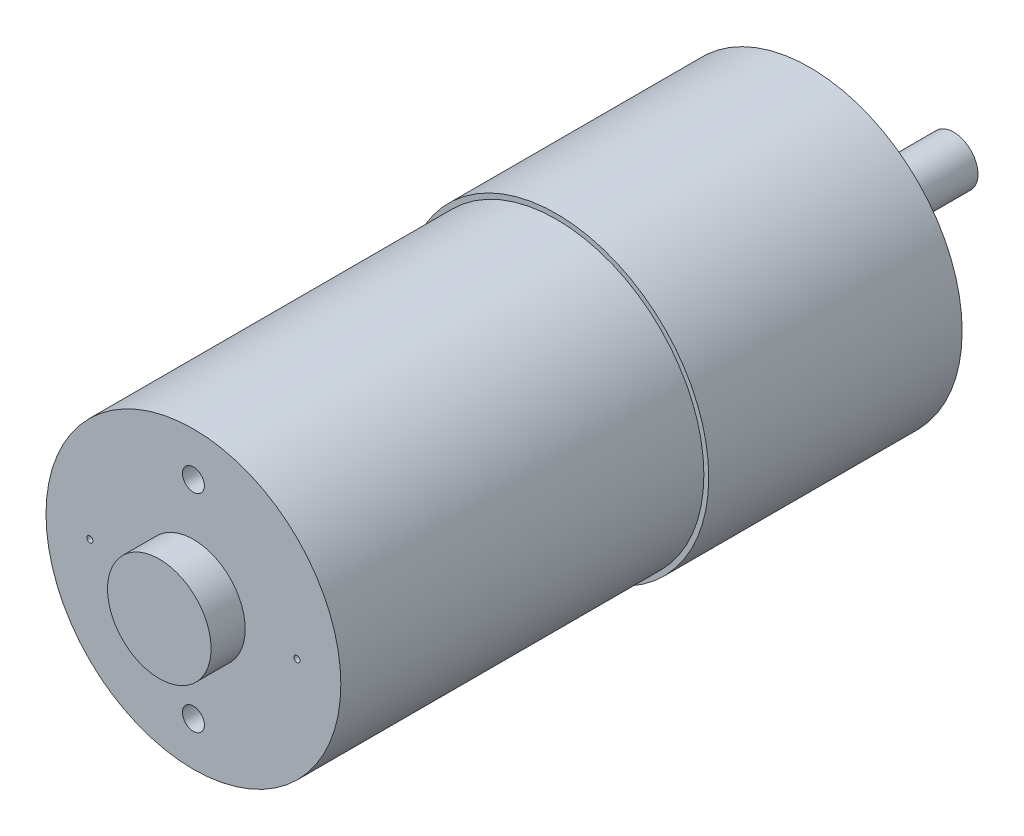
SolidWorks part; units mm, degrees
ref_plane "Plano frontal" through (0, 0, 0) normal (0, 0, 1) x (1, 0, 0)
ref_plane "Plano superior" through (0, 0, 0) normal (0, 1, 0) x (1, 0, 0)
ref_plane "Plano direito" through (0, 0, 0) normal (1, 0, 0) x (0, 0, -1)
sketch "Esboço1" plane through (0, 0, 0) normal (0, 0, 1) x (1, 0, 0)
  line L0 (0, 0) -> (0, 8.5) construction
  line L1 (0, 0) -> (0, -8.5) construction
  line L2 (0, 0) -> (8.5, 0) construction
  line L3 (0, 0) -> (-8.5, 0) construction
  circle A0 centre (0, 0) radius 12.5
  circle A1 centre (0, 8.5) radius 0.9
  circle A2 centre (0, -8.5) radius 0.9
  circle A3 centre (8.5, 0) radius 0.25
  circle A4 centre (-8.5, 0) radius 0.25
  dimension "D1" = 25
  dimension "D4" = 1.8
  dimension "D5" = 1.8
  dimension "D8" = 0.5
  dimension "D9" = 0.5
  dimension "D2" = 8.5
  dimension "D3" = 8.5
  dimension "D6" = 8.5
  dimension "D7" = 8.5
extrude "Ressalto-extrusão1" add sketch "Esboço1" along normal blind 50.6
sketch "Esboço2" plane through (0, 0, 0) normal (0, 0, 1) x (1, 0, 0)
  circle A0 centre (0, 0) radius 3.5
  circle A1 centre (0, 0) radius 2
  dimension "D1" = 7
  dimension "D2" = 4
extrude "Ressalto-extrusão2" add sketch "Esboço2" against normal blind 2 contours A0
sketch "Esboço3" plane through (0, 0, 0) normal (0, 0, 1) x (1, 0, 0)
  circle A0 centre (0, 0) radius 2
  dimension "D1" = 4
extrude "Ressalto-extrusão3" add sketch "Esboço3" against normal blind 11.8 contours A0
ref_plane "Plano1" through (0, 0, 50.6) normal (0, 0, 1) x (1, 0, 0)
sketch "Esboço4" plane through (0, 0, 50.6) normal (0, 0, 1) x (1, 0, 0)
  circle A0 centre (0, 0) radius 4.25
  dimension "D1" = 8.5
extrude "Ressalto-extrusão4" add sketch "Esboço4" along normal blind 2.8
sketch "Esboço6" plane through (0, 0, 50.6) normal (0, 0, 1) x (1, 0, 0)
  circle A0 centre (0, 0) radius 12.1
  circle A1 centre (0, 0) radius 12.5
  dimension "D1" = 24.2
extrude "Corte-extrusão1" cut sketch "Esboço6" against normal blind 29.8
